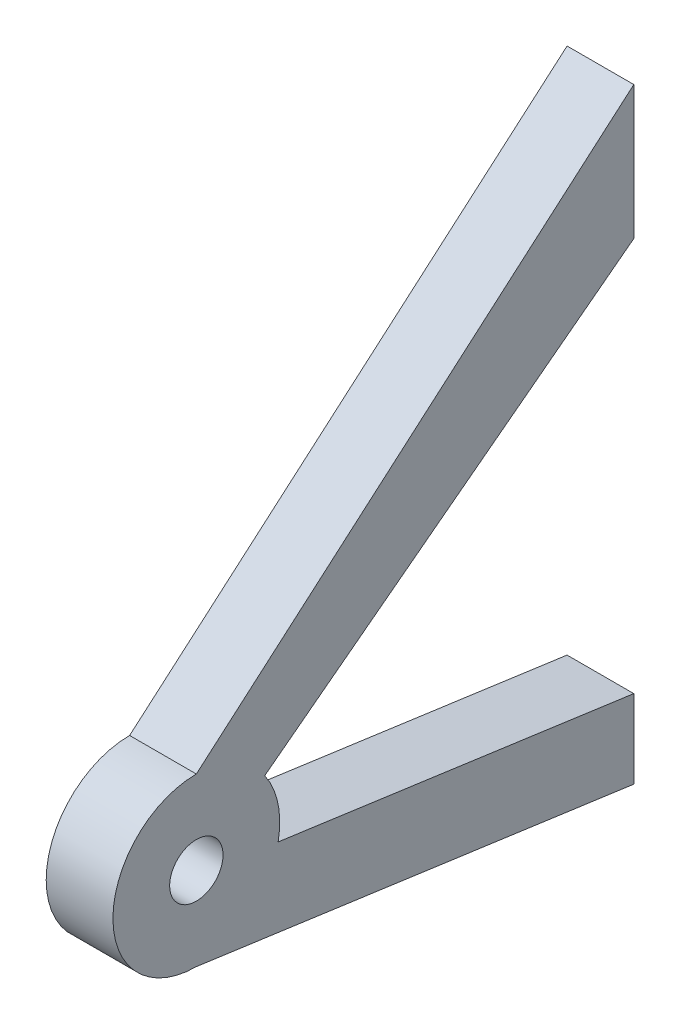
SolidWorks part; units mm, degrees
material "ABS PC"
ref_plane "Front Plane" through (0, 0, 0) normal (0, 0, 1) x (1, 0, 0)
ref_plane "Top Plane" through (0, 0, 0) normal (0, 1, 0) x (1, 0, 0)
ref_plane "Right Plane" through (0, 0, 0) normal (1, 0, 0) x (0, 0, -1)
sketch "Sketch1" plane through (-21.5772, 0, 0) normal (1, 0, 0) x (0, 0, -1)
  line L0 (-164.0139, 25.3566) -> (-122.3872, 61.3617)
  line L1 (-122.3872, 61.3617) -> (-122.3872, 1.1453)
  line L2 (-101.991, 1.1453) -> (-132.598, 1.1453) construction
  line L3 (-122.3872, 3.1229) -> (-122.3872, -3.6172) construction
  line L4 (-122.3872, 3.703) -> (-164.0139, 9.4816)
  line L5 (-122.3872, 48.6685) -> (-157.5073, 21.9654)
  line L6 (-156.2295, 15.8678) -> (-122.3872, 11.1698)
  circle A0 centre (-164.0139, 17.4191) radius 2.54
  arc A1 (-164.0139, 25.3566) -> (-164.0139, 9.4816) centre (-164.0139, 17.4191) ccw
  arc A2 (-157.5073, 21.9654) -> (-156.2295, 15.8678) centre (-164.0139, 17.4191) cw
  arc A3 (-156.2295, 15.8678) -> (-157.5073, 21.9654) centre (-164.0139, 17.4191) ccw
  dimension "D1" = 5.08
  dimension "D2" = 15.875
extrude "Boss-Extrude1" add sketch "Sketch1" against normal blind 6.35 contours A2 L5 L1 L0 A1 L4 L6 A0
